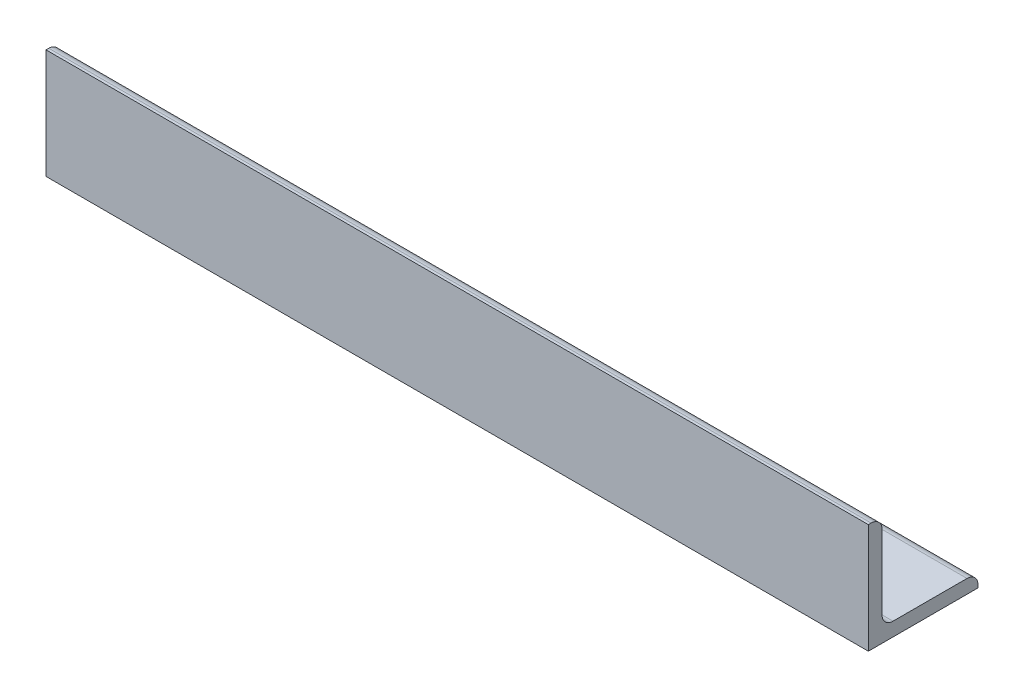
SolidWorks part; units mm, degrees
ref_plane "Front Plane" through (0, 0, 0) normal (0, 0, 1) x (1, 0, 0)
ref_plane "Top Plane" through (0, 0, 0) normal (0, 1, 0) x (1, 0, 0)
ref_plane "Right Plane" through (0, 0, 0) normal (1, 0, 0) x (0, 0, -1)
sketch "Sketch1" plane through (0, 0, 0) normal (1, 0, 0) x (0, 0, -1)
  line L0 (0, 0) -> (0, 25.4)
  line L1 (0, 25.4) -> (0.635, 25.4)
  line L2 (3.175, 22.86) -> (3.175, 5.715)
  line L3 (5.715, 3.175) -> (22.86, 3.175)
  line L4 (25.4, 0.635) -> (25.4, 0)
  line L5 (25.4, 0) -> (0, 0)
  arc A0 (22.86, 3.175) -> (25.4, 0.635) centre (22.86, 0.635) cw
  arc A1 (3.175, 5.715) -> (5.715, 3.175) centre (5.715, 5.715) ccw
  arc A2 (0.635, 25.4) -> (3.175, 22.86) centre (0.635, 22.86) cw
  point P13 (3.175, 25.4)
  dimension "D3" = 2.54
  dimension "D1" = 3.175
  dimension "D2" = 25.4
extrude "Boss-Extrude1" add sketch "Sketch1" along normal blind 190.5
